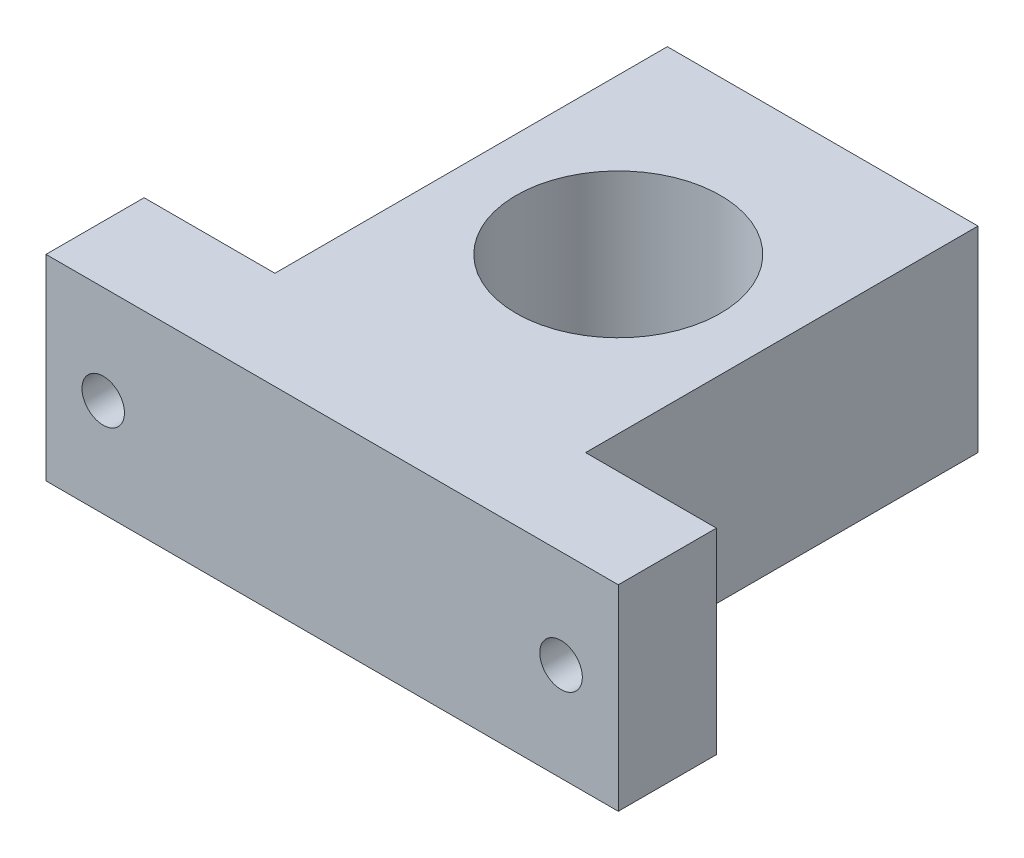
SolidWorks part; units mm, degrees
ref_plane "前视基准面" through (0, 0, 0) normal (0, 0, 1) x (1, 0, 0)
ref_plane "上视基准面" through (0, 0, 0) normal (0, 1, 0) x (1, 0, 0)
ref_plane "右视基准面" through (0, 0, 0) normal (1, 0, 0) x (0, 0, -1)
sketch "草图1" plane through (0, 0, 0) normal (0, 1, 0) x (1, 0, 0)
  line L0 (35, 0) -> (-35, 0)
  line L1 (-35, 0) -> (-35, 12)
  line L2 (-35, 12) -> (-19, 12)
  line L3 (-19, 12) -> (-19, 60)
  line L4 (-19, 60) -> (19, 60)
  line L5 (0, 57.9337) -> (0, -31.5239) construction
  line L6 (19, 12) -> (19, 60)
  line L7 (35, 12) -> (19, 12)
  line L8 (35, 0) -> (35, 12)
  circle A0 centre (0, 35) radius 12.5
  point P11 (0, 60)
  point P12 (0, 0)
  dimension "D5" = 25
  dimension "D6" = 35
  dimension "D1" = 70
  dimension "D2" = 12
  dimension "D3" = 38
  dimension "D4" = 60
extrude "凸台-拉伸1" add sketch "草图1" along normal blind 24
sketch "草图2" plane through (0, 0, -12) normal (0, 0, -1) x (-1, 0, 0)
  line L0 (-35, 12) -> (42.2085, 12) construction
  line L1 (-35, 24) -> (-35, 0) construction
  line L2 (0, 24) -> (0, -12.3652) construction
  line L3 (-19, 24) -> (19, 24) construction
  circle A0 centre (-28, 12) radius 2.6
  circle A1 centre (28, 12) radius 2.6
  dimension "D1" = 5.2
  dimension "D2" = 56
extrude "切除-拉伸1" cut sketch "草图2" against normal blind 24
